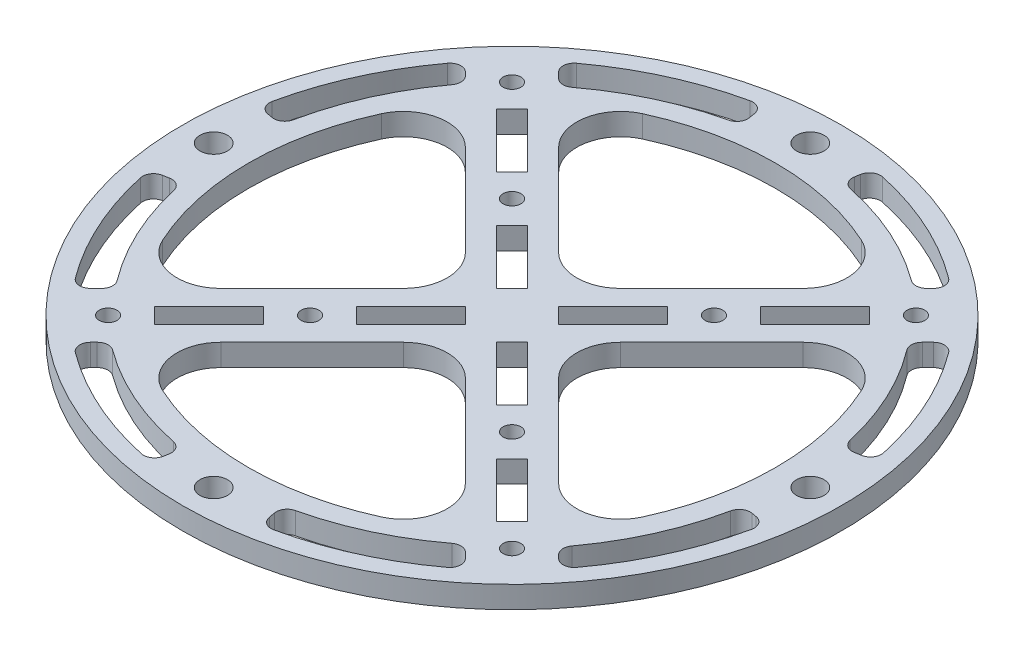
SolidWorks part; units mm, degrees
ref_plane "Front Plane" through (0, 0, 0) normal (0, 0, 1) x (1, 0, 0)
ref_plane "Top Plane" through (0, 0, 0) normal (0, 1, 0) x (1, 0, 0)
ref_plane "Right Plane" through (0, 0, 0) normal (1, 0, 0) x (0, 0, -1)
sketch "Sketch1" plane through (0, 0, 0) normal (0, 1, 0) x (1, 0, 0)
  circle A0 centre (0, 0) radius 150
  dimension "D1" = 300
extrude "Boss-Extrude1" add sketch "Sketch1" along normal blind 10
sketch "Sketch2" plane through (0, 10, 0) normal (0, 1, 0) x (1, 0, 0)
  line L0 (0, 135.7645) -> (135.7645, 0) construction
  line L1 (135.7645, 0) -> (0, -135.7645) construction
  line L2 (0, -135.7645) -> (-135.7645, 0) construction
  line L3 (-135.7645, 0) -> (0, 135.7645) construction
  line L4 (0, 0) -> (67.8823, 67.8823) construction
  line L5 (0, 0) -> (0, 55.7409) construction
  circle A0 centre (-135.7645, 0) radius 6.25
  circle A1 centre (0, -135.7645) radius 6.25
  circle A2 centre (135.7645, 0) radius 6.25
  circle A4 centre (0, 135.7645) radius 6.25
  dimension "D13" = 12.5
  dimension "D2" = 12.5
  dimension "D3" = 12.5
  dimension "D4" = 12.5
  dimension "D14" = 96
  dimension "D15" = 192
  dimension "D16" = 192
  dimension "D17" = 96
  dimension "D18" = 45
extrude "Cut-Extrude1" cut sketch "Sketch2" against normal through all
sketch "Sketch3" plane through (0, 0, 0) normal (1, 0, 0) x (0, 0, -1)
  line L0 (0, 0) -> (0, 10) construction
  line L1 (150, 10) -> (-150, 10) construction
sketch "Sketch4" plane through (0, 10, 0) normal (0, 1, 0) x (1, 0, 0)
  line L0 (0, 0) -> (-178.5778, 178.5778) construction
  line L1 (-31.8198, 38.8909) -> (-7.0711, 14.1421)
  line L2 (-252.9476, 0) -> (0, 0) construction
  line L3 (-31.8198, 38.8909) -> (-38.8909, 31.8198)
  line L4 (-7.0711, 14.1421) -> (-14.1421, 7.0711)
  line L5 (-38.8909, 31.8198) -> (-14.1421, 7.0711)
  line L6 (-31.8198, 38.8909) -> (-14.1421, 7.0711) construction
  line L7 (-7.0711, 14.1421) -> (-38.8909, 31.8198) construction
  line L8 (-77.7817, 84.8528) -> (-53.033, 60.1041)
  line L9 (-77.7817, 84.8528) -> (-84.8528, 77.7817)
  line L10 (-53.033, 60.1041) -> (-60.1041, 53.033)
  line L11 (-84.8528, 77.7817) -> (-60.1041, 53.033)
  line L12 (-77.7817, 84.8528) -> (-60.1041, 53.033) construction
  line L13 (-53.033, 60.1041) -> (-84.8528, 77.7817) construction
  circle A0 centre (-45.9619, 45.9619) radius 4.05
  circle A1 centre (-91.9239, 91.9239) radius 4.05
  point P5 (-22.981, 22.981)
  point P6 (-68.9429, 68.9429)
  dimension "D5" = 8.1
  dimension "D9" = 8.1
  dimension "D1" = 45
  dimension "D2" = 15
  dimension "D3" = 50
  dimension "D4" = 65
  dimension "D6" = 80
  dimension "D7" = 115
  dimension "D8" = 130
  dimension "D10" = 10
  dimension "D11" = 10
  dimension "D12" = 5
  dimension "D13" = 5
extrude "Cut-Extrude2" cut sketch "Sketch4" against normal through all
pattern_circular "CirPattern1" count 4 over 360 about axis through (0, 0, 0) along (0, 1, 0) of "Cut-Extrude2"
sketch "Sketch5" plane through (0, 10, 0) normal (0, 1, 0) x (1, 0, 0)
  line L0 (0, 0) -> (-106.066, 106.066) construction
  line L1 (0, 0) -> (-106.066, -106.066) construction
  line L2 (0, 0) -> (-120, 0) construction
  line L3 (-21.2132, 0) -> (-116.141, 94.9278)
  line L4 (-21.2132, 0) -> (-116.141, -94.9278)
  line L5 (0, 0) -> (-139.8958, 24.6674)
  line L6 (-139.8958, 24.6674) -> (1.6645, -0.2935)
  line L7 (1.6645, -0.2935) -> (-139.7943, -25.2365)
  circle A0 centre (0, 0) radius 150 construction
  circle A1 centre (0, 0) radius 120
  circle A2 centre (0, 0) radius 142.054
  circle A3 centre (-1.2146, 1.2146) radius 128.3054
  dimension "D1" = 240
  dimension "D2" = 15
  dimension "D3" = 15
  dimension "D4" = 10
  dimension "D5" = 10
extrude "Cut-Extrude3" cut sketch "Sketch5" against normal through all contours L3 A1 L5 | L5 A1 L7 L4 L3 | L7 A1 L4 | A3 L7 A2 L4 | A3 L3 A2 L5
pattern_circular "CirPattern2" count 4 over 360 about axis through (0, 0, 0) along (0, 1, 0) of "Cut-Extrude3"
fillet "Fillet1" radius 20 12 edges at (-21.2132, 5, 0) (-94.7939, 5, 73.5807) (-94.7939, 5, -73.5807) (73.5807, 5, 94.7939) (-73.5807, 5, 94.7939) (94.7939, 5, 73.5807) (94.7939, 5, -73.5807) (73.5807, 5, -94.7939) (-73.5807, 5, -94.7939) (0, 5, 21.2132) (21.2132, 5, 0) (0, 5, -21.2132)
fillet "Fillet2" radius 5 32 edges at (-100.8448, 5, 79.6316) (-110.4923, 5, 89.2791) (-127.2109, 5, 23.0177) (-139.7943, 5, 25.2365) (-127.7381, 5, -22.5237) (-139.8958, 5, -24.6674) (-101.9247, 5, -80.7115) (-110.4923, 5, -89.2791) (25.2365, 5, 139.7943) (-24.6674, 5, 139.8958) (-22.5237, 5, 127.7381) (-80.7115, 5, 101.9247) (-89.2791, 5, 110.4923) (23.0177, 5, 127.2109) (89.2791, 5, 110.4923) (79.6316, 5, 100.8448) (110.4923, 5, 89.2791) (101.9247, 5, 80.7115) (139.8958, 5, 24.6674) (127.7381, 5, 22.5237) (127.2109, 5, -23.0177) (100.8448, 5, -79.6316) (110.4923, 5, -89.2791) (139.7943, 5, -25.2365) (80.7115, 5, -101.9247) (24.6674, 5, -139.8958) (-79.6316, 5, -100.8448) (-23.0177, 5, -127.2109) (-25.2365, 5, -139.7943) (89.2791, 5, -110.4923) (22.5237, 5, -127.7381) (-89.2791, 5, -110.4923)
